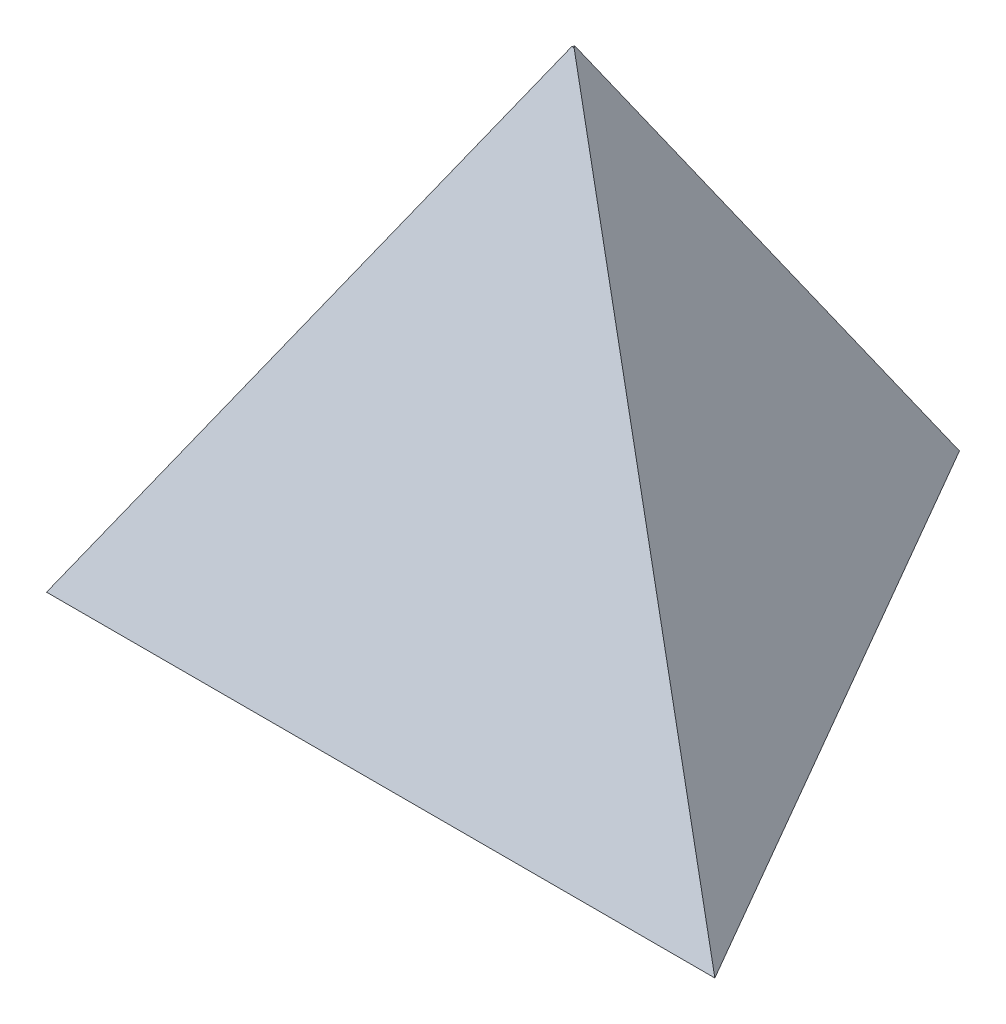
SolidWorks part; units mm, degrees
ref_plane "Front Plane" through (0, 0, 0) normal (0, 0, 1) x (1, 0, 0)
ref_plane "Top Plane" through (0, 0, 0) normal (0, 1, 0) x (1, 0, 0)
ref_plane "Right Plane" through (0, 0, 0) normal (1, 0, 0) x (0, 0, -1)
sketch "Sketch1" plane through (0, 0, 0) normal (0, 1, 0) x (1, 0, 0)
  line L1 (40, -23.094) -> (0, 46.188)
  line L2 (0, 46.188) -> (-40, -23.094)
  line L3 (-40, -23.094) -> (40, -23.094)
  circle A0 centre (0, 0) radius 23.094 construction
  dimension "D1" = 80
extrude "Boss-Extrude1" add sketch "Sketch1" along normal blind 65 draft 19.5
shell "Shell1" thickness 2
ref_plane "Plane2" through (0, 0, -46.188) normal (-0.5, 0, 0.866) x (0.866, 0, 0.5)
sketch "Sketch4" plane through (0, 0, 0) normal (0, 1, 0) x (1, 0, 0)
  line L4 (30, -17.3205) -> (0, 34.641)
  line L5 (0, 34.641) -> (-30, -17.3205)
  line L6 (37.1911, -21.4723) -> (0, 42.9446)
  line L7 (-37.1911, -21.4723) -> (37.1911, -21.4723)
  line L8 (0, 42.9446) -> (-37.1911, -21.4723)
  line L9 (37.1911, -21.4723) -> (0, 42.9446)
  line L10 (-37.1911, -21.4723) -> (37.1911, -21.4723)
  line L11 (0, 42.9446) -> (-37.1911, -21.4723)
  line L12 (-30, -17.3205) -> (30, -17.3205)
  circle A0 centre (0, 0) radius 17.3205 construction
  dimension "D2" = 60
  dimension "D1" = 0.5
